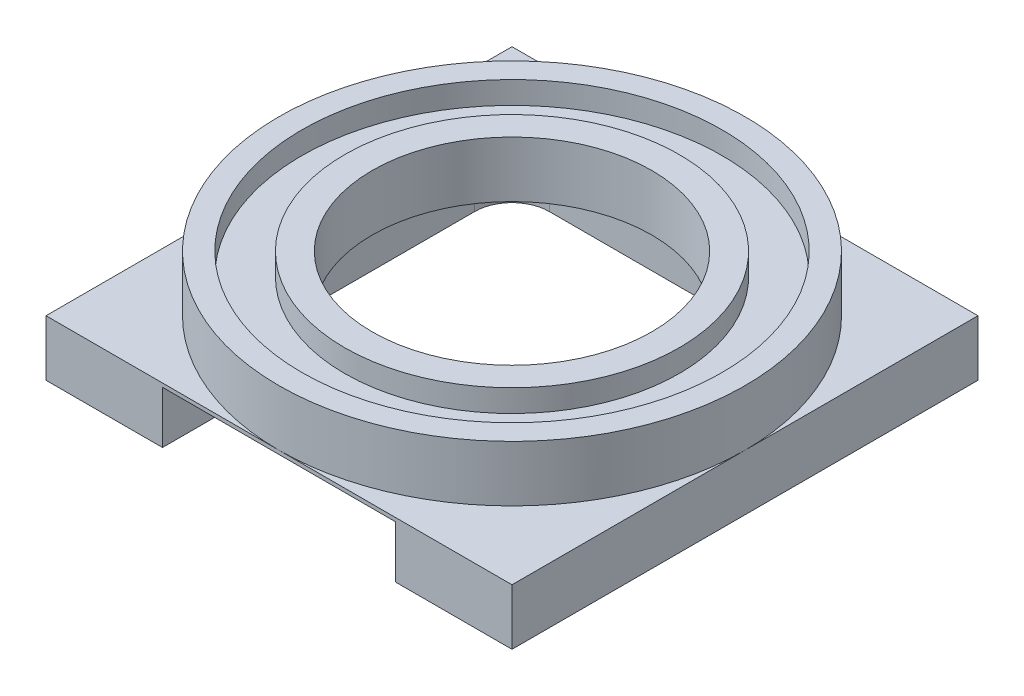
SolidWorks part; units mm, degrees
ref_plane "Ebene vorne" through (0, 0, 0) normal (0, 0, 1) x (1, 0, 0)
ref_plane "Ebene oben" through (0, 0, 0) normal (0, 1, 0) x (1, 0, 0)
ref_plane "Ebene rechts" through (0, 0, 0) normal (1, 0, 0) x (0, 0, -1)
sketch "Skizze1" plane through (0, 0, 0) normal (0, 1, 0) x (1, 0, 0)
  line L0 (0, -125) -> (0, 125)
  circle A1 centre (0, 0) radius 89.75
  circle A2 centre (0, 0) radius 125
  circle A3 centre (0, 0) radius 75
  circle A4 centre (0, 0) radius 112.75
  point P3 (0, 0)
  dimension "D2" = 179.5
  dimension "D3" = 225.5
  dimension "D1" = 250
extrude "Aufsatz-Linear austragen1" add sketch "Skizze1" along normal blind 30 contours A4 L0 A2 | A4 L0 A2 | L0 A4 A1 | L0 A4 A1 | A3 L0 A1 | A3 L0 A1
sketch "Skizze2" plane through (0, 30, 0) normal (0, 1, 0) x (1, 0, 0)
  circle A0 centre (0, 0) radius 89.75
  circle A1 centre (0, 0) radius 112.75
  dimension "D1" = 225.5
  dimension "D2" = 179.5
extrude "Schnitt-Linear austragen1" cut sketch "Skizze2" against normal blind 12
sketch "Skizze3" plane through (0, 0, 0) normal (0, -1, 0) x (1, 0, 0)
  line L1 (-125, -125) -> (125, -125)
  line L2 (-125, -125) -> (-125, 125)
  line L3 (-125, 125) -> (125, 125)
  line L4 (125, -125) -> (125, 125)
  line L5 (-125, -125) -> (125, 125) construction
  line L6 (-125, 125) -> (125, -125) construction
  line L7 (-68.3883, -88.3883) -> (68.3883, -88.3883)
  line L8 (-88.3883, -68.3883) -> (-88.3883, 68.3883)
  line L9 (-68.3883, 88.3883) -> (68.3883, 88.3883)
  line L10 (88.3883, -68.3883) -> (88.3883, 68.3883)
  line L11 (-88.3883, -88.3883) -> (88.3883, 88.3883) construction
  line L12 (-88.3883, 88.3883) -> (88.3883, -88.3883) construction
  circle A0 centre (0, 0) radius 75
  circle A1 centre (0, 0) radius 125 construction
  arc A2 (-68.3883, -88.3883) -> (-88.3883, -68.3883) centre (-68.3883, -68.3883) cw
  arc A3 (68.3883, -88.3883) -> (88.3883, -68.3883) centre (68.3883, -68.3883) ccw
  arc A4 (68.3883, 88.3883) -> (88.3883, 68.3883) centre (68.3883, 68.3883) cw
  arc A5 (-88.3883, 68.3883) -> (-68.3883, 88.3883) centre (-68.3883, 68.3883) cw
  circle M15 centre (0, 0) radius 125
  dimension "D1" = 20
extrude "Aufsatz-Linear austragen2" add sketch "Skizze3" along normal blind 30 contours L8 A5 L9 A4 L10 A3 L7 A2 M15 | L3 L2 M15 | L4 L3 M15 | L1 L4 M15 | L2 L1 M15
sketch "Skizze4" plane through (0, 0, 125) normal (0, 0, 1) x (1, 0, 0)
  line L0 (62.5, -2) -> (-62.5, -2)
  line L3 (-62.5, -2) -> (-62.5, -30)
  line L4 (-125, -30) -> (125, -30) construction
  line L5 (-62.5, -30) -> (62.5, -30)
  line L6 (62.5, -30) -> (62.5, -2)
  line L7 (-125, 0) -> (0, 0) construction
  point P3 (0, 0)
  dimension "D1" = 2
extrude "Schnitt-Linear austragen2" cut sketch "Skizze4" against normal blind 37
